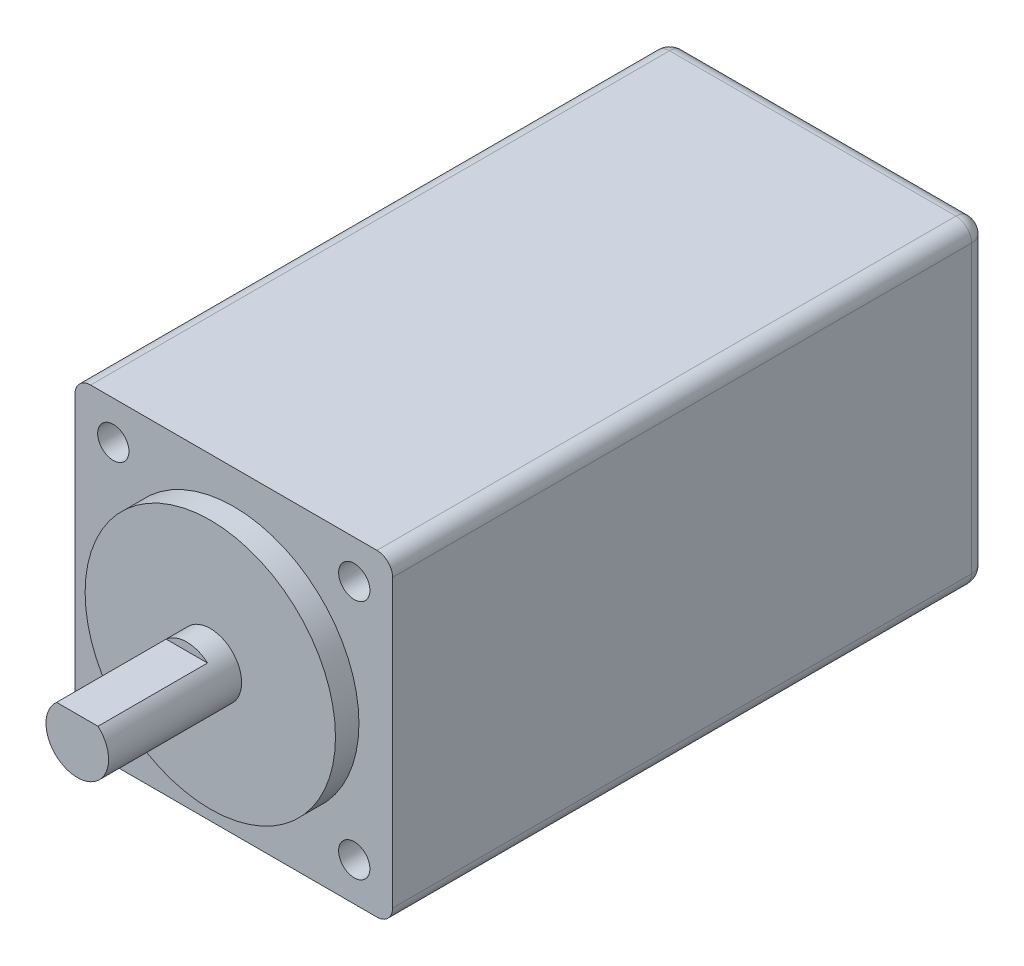
SolidWorks part; units mm, degrees
ref_plane "Front Plane" through (0, 0, 0) normal (0, 0, 1) x (1, 0, 0)
ref_plane "Top Plane" through (0, 0, 0) normal (0, 1, 0) x (1, 0, 0)
ref_plane "Right Plane" through (0, 0, 0) normal (1, 0, 0) x (0, 0, -1)
sketch "Sketch1" plane through (0, 0, 0) normal (0, 0, 1) x (1, 0, 0)
  line L1 (-10.15, -10.15) -> (10.15, -10.15)
  line L2 (-10.15, -10.15) -> (-10.15, 10.15)
  line L3 (-10.15, 10.15) -> (10.15, 10.15)
  line L4 (10.15, -10.15) -> (10.15, 10.15)
  line L5 (-10.15, -10.15) -> (10.15, 10.15) construction
  line L6 (-10.15, 10.15) -> (10.15, -10.15) construction
  point P0 (0, 0)
  dimension "D1" = 20.3
  dimension "D2" = 20.3
extrude "Boss-Extrude1" add sketch "Sketch1" along normal blind 38
sketch "Sketch2" plane through (0, 0, 38) normal (0, 0, 1) x (1, 0, 0)
  circle A0 centre (0, 0) radius 8
  dimension "D1" = 16
extrude "Boss-Extrude2" add sketch "Sketch2" along normal blind 1.5
sketch "Sketch3" plane through (0, 0, 39.5) normal (0, 0, 1) x (1, 0, 0)
  circle A0 centre (0, 0) radius 2
  dimension "D1" = 4
extrude "Boss-Extrude3" add sketch "Sketch3" along normal blind 8.5
sketch "Sketch4" plane through (0, 0, 0) normal (1, 0, 0) x (0, 0, -1)
  line L1 (-48, 2) -> (-41, 2)
  line L2 (-48, 2) -> (-48, 1.5)
  line L3 (-48, 1.5) -> (-41, 1.5)
  line L4 (-41, 2) -> (-41, 1.5)
  dimension "D1" = 7
  dimension "D2" = 0.5
extrude "Cut-Extrude1" cut sketch "Sketch4" against normal mid plane 10
sketch "Sketch5" plane through (0, 0, 38) normal (0, 0, 1) x (1, 0, 0)
  line L1 (-7.7, -7.7) -> (7.7, -7.7) construction
  line L2 (-7.7, -7.7) -> (-7.7, 7.7) construction
  line L3 (-7.7, 7.7) -> (7.7, 7.7) construction
  line L4 (7.7, -7.7) -> (7.7, 7.7) construction
  line L5 (-7.7, -7.7) -> (7.7, 7.7) construction
  line L6 (-7.7, 7.7) -> (7.7, -7.7) construction
  circle A0 centre (-7.7, 7.7) radius 1
  circle A1 centre (7.7, 7.7) radius 1
  circle A2 centre (7.7, -7.7) radius 1
  circle A3 centre (-7.7, -7.7) radius 1
  point P0 (0, 0)
  dimension "D3" = 2
  dimension "D1" = 15.4
  dimension "D2" = 15.4
  dimension "D4" = 4
extrude "Cut-Extrude2" cut sketch "Sketch5" against normal blind 2.5
fillet "Fillet1" radius 1 8 edges at (0, 10.15, 0) (-10.15, 0, 0) (0, -10.15, 0) (10.15, 0, 0) (-10.15, -10.15, 19) (10.15, -10.15, 19) (-10.15, 10.15, 19) (10.15, 10.15, 19)
